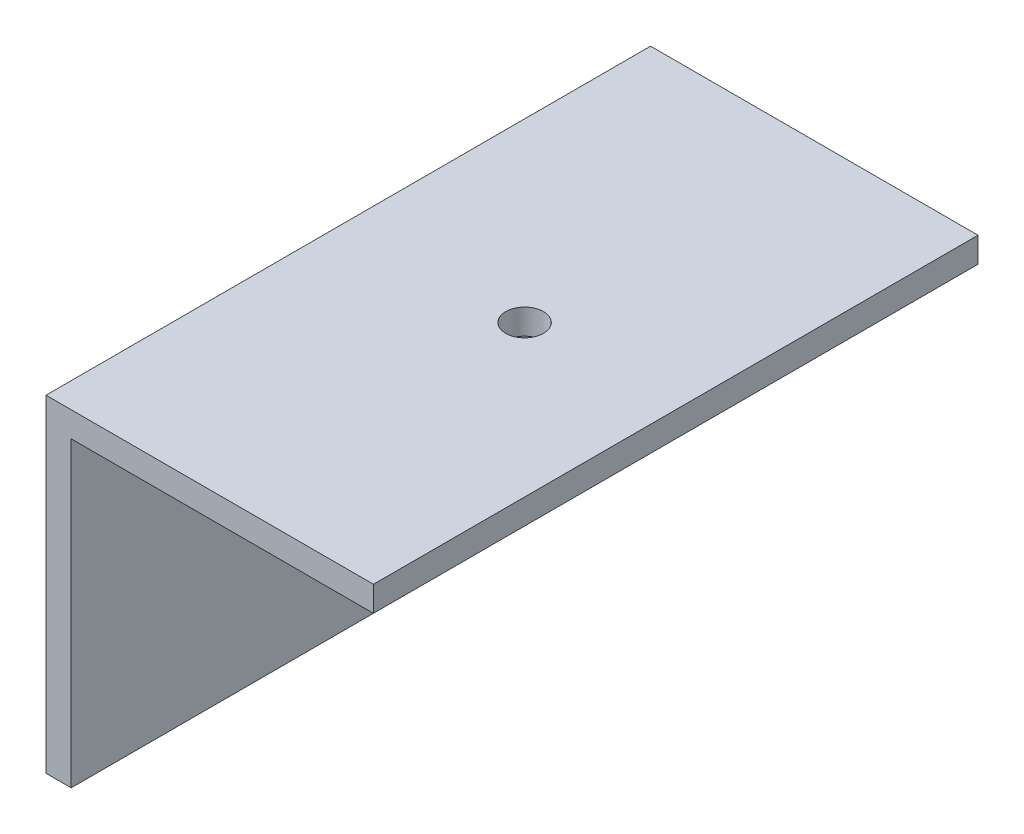
SolidWorks part; units mm, degrees
ref_plane "Front Plane" through (0, 0, 0) normal (0, 0, 1) x (1, 0, 0)
ref_plane "Top Plane" through (0, 0, 0) normal (0, 1, 0) x (1, 0, 0)
ref_plane "Right Plane" through (0, 0, 0) normal (1, 0, 0) x (0, 0, -1)
sketch "Sketch1" plane through (0, 0, 0) normal (0, 0, 1) x (1, 0, 0)
  line L0 (0, 0) -> (0, 165.1)
  line L1 (0, -104.775) -> (0, 104.775) construction
  line L2 (0, 165.1) -> (165.1, 165.1)
  line L3 (165.1, 165.1) -> (165.1, 152.4)
  line L4 (165.1, 152.4) -> (12.7, 152.4)
  line L5 (12.7, 152.4) -> (12.7, 0)
  line L6 (104.775, 0) -> (-104.775, 0) construction
  line L7 (12.7, 0) -> (0, 0)
  dimension "D1" = 152.4
  dimension "D2" = 152.4
  dimension "D3" = 12.7
  dimension "D4" = 12.7
extrude "Boss-Extrude1" add sketch "Sketch1" along normal blind 304.8
sketch "Sketch2" plane through (0, 152.4, 0) normal (0, -1, 0) x (1, 0, 0)
  line L0 (12.7, 304.8) -> (165.1, 0) construction
  circle A0 centre (88.9, 152.4) radius 9.525
  dimension "D1" = 19.05
extrude "Cut-Extrude1" cut sketch "Sketch2" against normal through all
